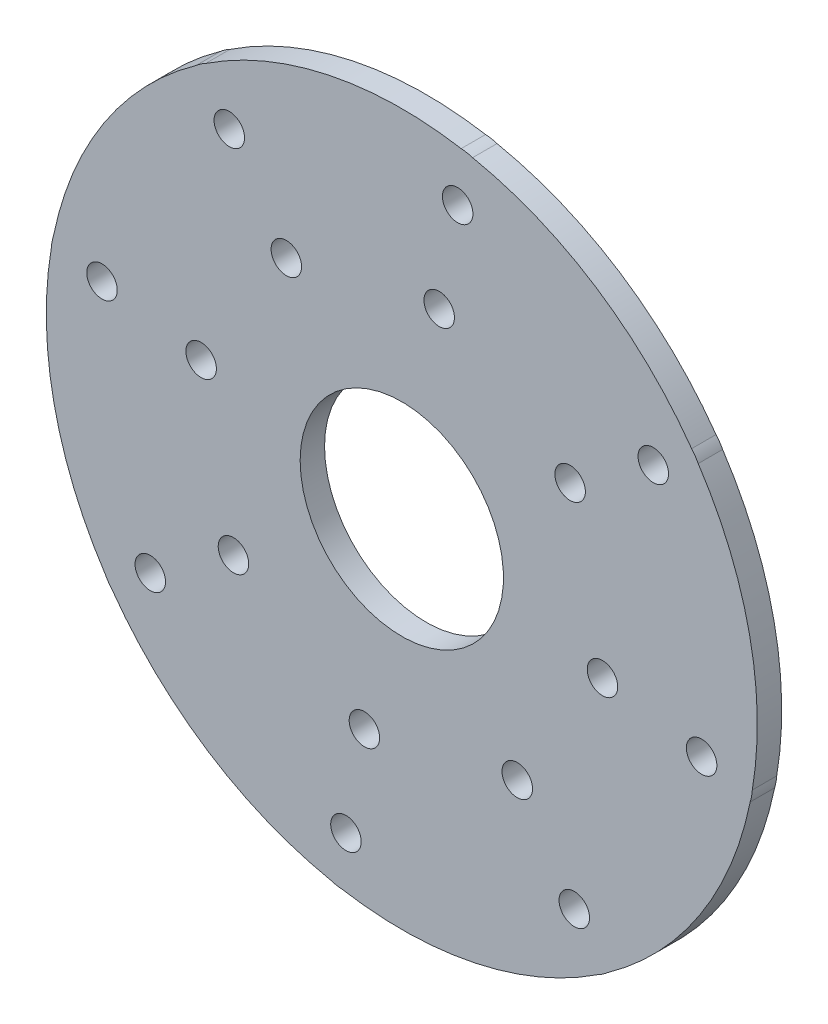
SolidWorks part; units mm, degrees
ref_plane "Front Plane" through (0, 0, 0) normal (0, 0, 1) x (1, 0, 0)
ref_plane "Top Plane" through (0, 0, 0) normal (0, 1, 0) x (1, 0, 0)
ref_plane "Right Plane" through (0, 0, 0) normal (1, 0, 0) x (0, 0, -1)
sketch "Sketch1" plane through (0, 0, 0) normal (0, 0, 1) x (1, 0, 0)
  line L0 (1.7447, 9.3638) -> (0, 0)
  circle A0 centre (0, 0) radius 3.175
  arc A1 (-6.2132, 9.2132) -> (-6.2855, 9.1641) centre (0, 0) ccw
  circle A2 centre (1.7447, 9.3638) radius 0.4763
  circle A3 centre (1.7447, 9.3638) radius 1.5875
  circle A4 centre (7.8549, 5.3875) radius 1.5875
  circle A5 centre (7.8549, 5.3875) radius 0.4763
  circle A6 centre (9.3638, -1.7447) radius 1.5875
  circle A7 centre (9.3638, -1.7447) radius 0.4762
  circle A8 centre (5.3875, -7.8549) radius 1.5875
  circle A9 centre (5.3875, -7.8549) radius 0.4763
  circle A10 centre (-1.7447, -9.3638) radius 1.5875
  circle A11 centre (-1.7447, -9.3638) radius 0.4762
  circle A12 centre (-7.8549, -5.3875) radius 1.5875
  circle A13 centre (-7.8549, -5.3875) radius 0.4763
  circle A14 centre (-9.3638, 1.7447) radius 1.5875
  circle A15 centre (-9.3638, 1.7447) radius 0.4763
  circle A16 centre (-5.3875, 7.8549) radius 1.5875
  circle A17 centre (-5.3875, 7.8549) radius 0.4762
  arc A18 (2.1213, 10.9081) -> (6.2674, 5.3875) centre (0.519, 5.3875) cw
  arc A19 (5.4528, 8.3375) -> (7.8549, 6.975) centre (7.8549, 9.7739) ccw
  arc A20 (9.7512, 2.0398) -> (10.4864, -0.6222) centre (12.4655, 1.3569) ccw
  arc A21 (9.2132, 6.2132) -> (8.2413, -0.6222) centre (4.1765, 3.4426) cw
  arc A22 (8.3375, -5.4528) -> (6.975, -7.8549) centre (9.7739, -7.8549) ccw
  arc A23 (10.9081, -2.1213) -> (5.3875, -6.2674) centre (5.3875, -0.519) cw
  arc A24 (2.0398, -9.7512) -> (-0.6222, -10.4864) centre (1.3569, -12.4655) ccw
  arc A25 (6.2132, -9.2132) -> (-0.6222, -8.2413) centre (3.4426, -4.1765) cw
  arc A26 (-5.4528, -8.3375) -> (-7.8549, -6.975) centre (-7.8549, -9.7739) ccw
  arc A27 (-2.1213, -10.9081) -> (-6.2674, -5.3875) centre (-0.519, -5.3875) cw
  arc A28 (-9.7512, -2.0398) -> (-10.4864, 0.6222) centre (-12.4655, -1.3569) ccw
  arc A29 (-9.2132, -6.2132) -> (-8.2413, 0.6222) centre (-4.1765, -3.4426) cw
  arc A30 (-8.3375, 5.4528) -> (-6.975, 7.8549) centre (-9.7739, 7.8549) ccw
  arc A31 (-10.9081, 2.1213) -> (-5.3875, 6.2674) centre (-5.3875, 0.519) cw
  arc A32 (-2.0398, 9.7512) -> (0.6222, 10.4864) centre (-1.3569, 12.4655) ccw
  arc A33 (-6.2132, 9.2132) -> (0.6222, 8.2413) centre (-3.4426, 4.1765) cw
  arc A34 (2.1213, 10.9081) -> (2.0355, 10.9245) centre (0, 0) ccw
  arc A35 (9.2132, 6.2132) -> (9.1641, 6.2855) centre (0, 0) ccw
  arc A36 (10.9081, -2.1213) -> (10.9245, -2.0355) centre (0, 0) ccw
  arc A37 (6.2132, -9.2132) -> (6.2855, -9.1641) centre (0, 0) ccw
  arc A38 (-2.1213, -10.9081) -> (-2.0355, -10.9245) centre (0, 0) ccw
  arc A39 (-9.2132, -6.2132) -> (-9.1641, -6.2855) centre (0, 0) ccw
  arc A40 (-10.9081, 2.1213) -> (-10.9245, 2.0355) centre (0, 0) ccw
  circle A41 centre (0, 0) radius 6.35
  circle A42 centre (1.1678, 6.2674) radius 0.4763
  circle A43 centre (5.2575, 3.606) radius 0.4762
  circle A44 centre (6.2674, -1.1678) radius 0.4763
  circle A45 centre (3.606, -5.2575) radius 0.4763
  circle A46 centre (-1.1678, -6.2674) radius 0.4763
  circle A47 centre (-5.2575, -3.606) radius 0.4763
  circle A48 centre (-6.2674, 1.1678) radius 0.4763
  circle A49 centre (-3.606, 5.2575) radius 0.4763
  point P30 (0, 0)
  point P79 (0, 0)
  point P104 (0, 0)
  dimension "D1" = 6.35
  dimension "D2" = 0.9525
  dimension "D4" = 7.9375
  dimension "D7" = 12.7
  dimension "D8" = 0.9525
  dimension "D3" = 9.525
  dimension "D5" = 8
  dimension "D6" = 8
  dimension "D9" = 8
extrude "Boss-Extrude1" add sketch "Sketch1" along normal blind 0.762
sketch "Sketch2" plane through (0, 0, 0.762) normal (0, 0, 1) x (1, 0, 0)
  circle A0 centre (0, 0) radius 11.1035
  circle A1 centre (0, 0) radius 9.7402
  circle A2 centre (1.7447, 9.3638) radius 0.4763
  circle A3 centre (7.8549, 5.3875) radius 0.4762
  circle A4 centre (9.3638, -1.7447) radius 0.4763
  circle A5 centre (5.3875, -7.8549) radius 0.4763
  circle A6 centre (-1.7447, -9.3638) radius 0.4763
  circle A7 centre (-7.8549, -5.3875) radius 0.4763
  circle A8 centre (-9.3638, 1.7447) radius 0.4763
  circle A9 centre (-5.3875, 7.8549) radius 0.4763
  point P24 (0, 0)
  arc M9 (5.4528, 8.3375) -> (2.2124, 10.8809) centre (0.519, 5.3875) ccw
  arc M10 (2.2124, 10.8809) -> (0.6222, 10.4864) centre (1.7447, 9.3638) ccw
  arc M11 (0.6222, 10.4864) -> (-2.0398, 9.7512) centre (-1.3569, 12.4655) cw
  arc M12 (-2.0398, 9.7512) -> (-6.1296, 9.2583) centre (-3.4426, 4.1765) ccw
  arc M13 (-6.1296, 9.2583) -> (-6.975, 7.8549) centre (-5.3875, 7.8549) ccw
  arc M14 (-6.975, 7.8549) -> (-8.3375, 5.4528) centre (-9.7739, 7.8549) cw
  arc M15 (-8.3375, 5.4528) -> (-10.8809, 2.2124) centre (-5.3875, 0.519) ccw
  arc M16 (-10.8809, 2.2124) -> (-10.4864, 0.6222) centre (-9.3638, 1.7447) ccw
  arc M17 (-10.4864, 0.6222) -> (-9.7512, -2.0398) centre (-12.4655, -1.3569) cw
  arc M18 (-9.7512, -2.0398) -> (-9.2583, -6.1296) centre (-4.1765, -3.4426) ccw
  arc M19 (-9.2583, -6.1296) -> (-7.8549, -6.975) centre (-7.8549, -5.3875) ccw
  arc M20 (-7.8549, -6.975) -> (-5.4528, -8.3375) centre (-7.8549, -9.7739) cw
  arc M21 (-5.4528, -8.3375) -> (-2.2124, -10.8809) centre (-0.519, -5.3875) ccw
  arc M22 (-2.2124, -10.8809) -> (-0.6222, -10.4864) centre (-1.7447, -9.3638) ccw
  arc M23 (-0.6222, -10.4864) -> (2.0398, -9.7512) centre (1.3569, -12.4655) cw
  arc M24 (2.0398, -9.7512) -> (6.1296, -9.2583) centre (3.4426, -4.1765) ccw
  arc M25 (6.1296, -9.2583) -> (6.975, -7.8549) centre (5.3875, -7.8549) ccw
  arc M26 (6.975, -7.8549) -> (8.3375, -5.4528) centre (9.7739, -7.8549) cw
  arc M27 (8.3375, -5.4528) -> (10.8809, -2.2124) centre (5.3875, -0.519) ccw
  arc M28 (10.8809, -2.2124) -> (10.4864, -0.6222) centre (9.3638, -1.7447) ccw
  arc M29 (10.4864, -0.6222) -> (9.7512, 2.0398) centre (12.4655, 1.3569) cw
  arc M30 (9.7512, 2.0398) -> (9.2583, 6.1296) centre (4.1765, 3.4426) ccw
  arc M31 (9.2583, 6.1296) -> (7.8549, 6.975) centre (7.8549, 5.3875) ccw
  arc M32 (7.8549, 6.975) -> (5.4528, 8.3375) centre (7.8549, 9.7739) cw
  dimension "D1" = 8
extrude "Boss-Extrude2" add sketch "Sketch2" against normal up to surface (0.762 mm away) contours A0 M13 M15 M14 | A0 M10 M12 M11 | A0 M31 M9 M32 | A0 M28 M30 M29 | A0 M25 M27 M26 | A0 M22 M24 M23 | A0 M19 M21 M20 | A0 M16 M18 M17
